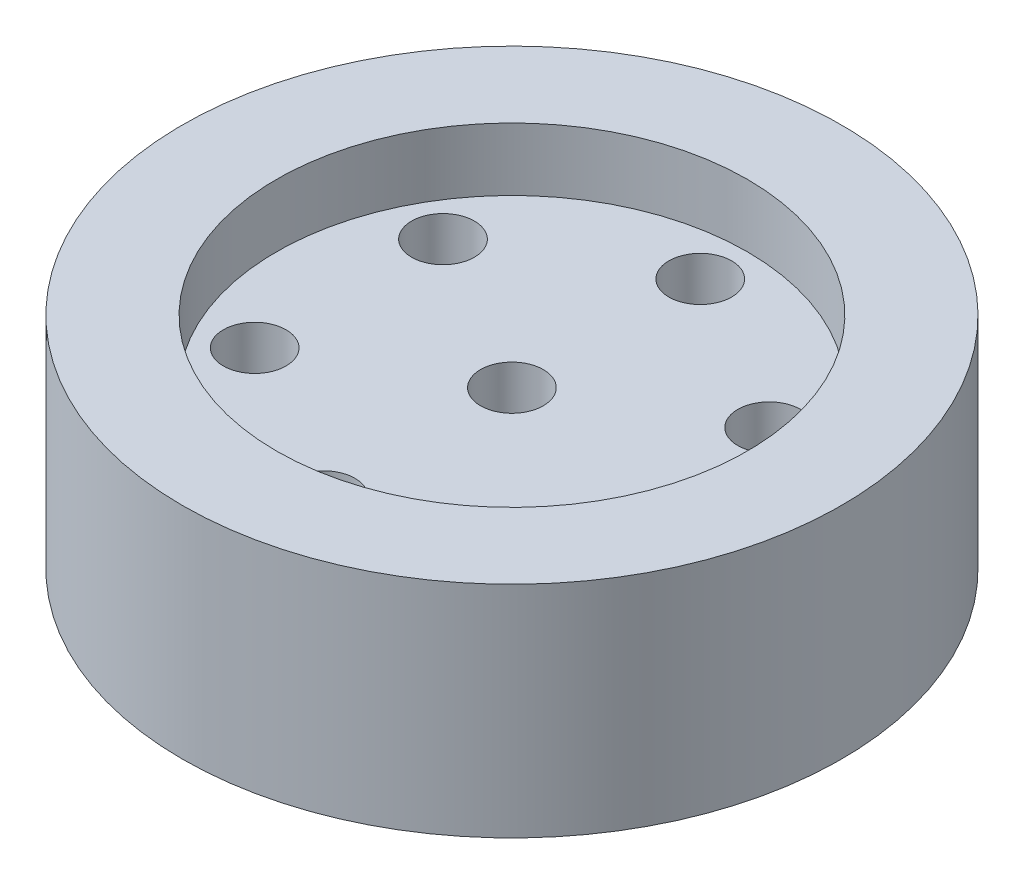
SolidWorks part; units mm, degrees
ref_plane "Front Plane" through (0, 0, 0) normal (0, 0, 1) x (1, 0, 0)
ref_plane "Top Plane" through (0, 0, 0) normal (0, 1, 0) x (1, 0, 0)
ref_plane "Right Plane" through (0, 0, 0) normal (1, 0, 0) x (0, 0, -1)
sketch "Sketch1" plane through (0, 0, 0) normal (0, 1, 0) x (1, 0, 0)
  circle A0 centre (0, 0) radius 21
  dimension "D1" = 42
extrude "Boss-Extrude1" add sketch "Sketch1" along normal blind 14
sketch "Sketch2" plane through (0, 14, 0) normal (0, 1, 0) x (1, 0, 0)
  circle A0 centre (0, 0) radius 15
  dimension "D1" = 30
extrude "Cut-Extrude1" cut sketch "Sketch2" against normal blind 4
sketch "Sketch3" plane through (0, 0, 0) normal (0, -1, 0) x (1, 0, 0)
  circle A0 centre (0, 0) radius 19
  circle A1 centre (0, 0) radius 5
  dimension "D1" = 10
  dimension "D2" = 38
extrude "Cut-Extrude2" cut sketch "Sketch3" against normal blind 4
sketch "Sketch4" plane through (0, 0, 0) normal (0, -1, 0) x (1, 0, 0)
  circle A0 centre (0, 0) radius 2
  dimension "D1" = 4
extrude "Cut-Extrude3" cut sketch "Sketch4" against normal through all
sketch "Sketch5" plane through (0, 4, 0) normal (0, -1, 0) x (1, 0, 0)
  circle A0 centre (0, 0) radius 12 construction
  circle A1 centre (0, 12) radius 2
  circle A2 centre (10.3923, 6) radius 2
  circle A3 centre (10.3923, -6) radius 2
  circle A4 centre (0, -12) radius 2
  circle A5 centre (-10.3923, -6) radius 2
  circle A6 centre (-10.3923, 6) radius 2
  point P18 (0, 0)
  dimension "D1" = 24
  dimension "D2" = 4
  dimension "D3" = 6
extrude "Cut-Extrude4" cut sketch "Sketch5" against normal through all
